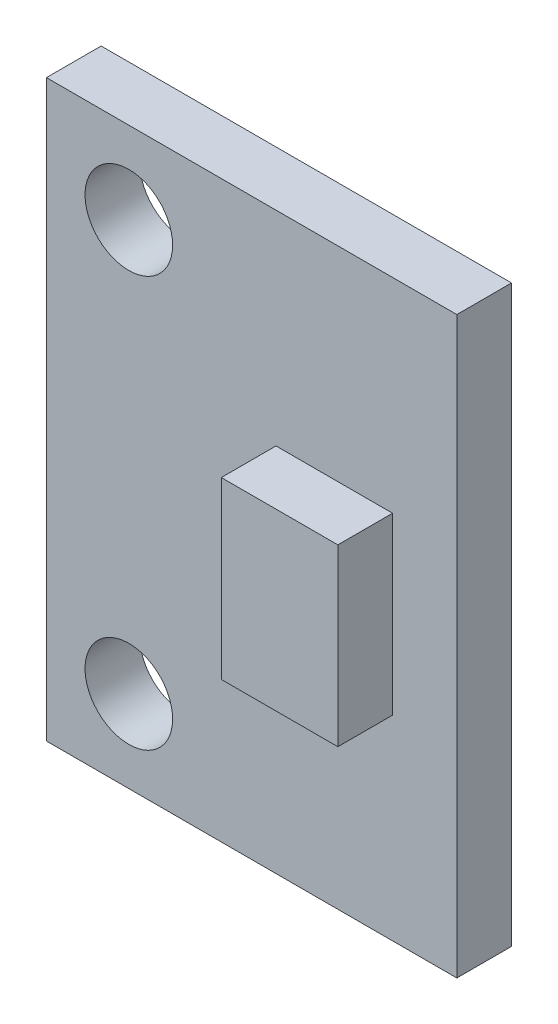
SolidWorks part; units mm, degrees
ref_plane "Front Plane" through (0, 0, 0) normal (0, 0, 1) x (1, 0, 0)
ref_plane "Top Plane" through (0, 0, 0) normal (0, 1, 0) x (1, 0, 0)
ref_plane "Right Plane" through (0, 0, 0) normal (1, 0, 0) x (0, 0, -1)
sketch "Sketch1" plane through (0, 0, 0) normal (0, 0, 1) x (1, 0, 0)
  line L0 (-81.4383, -168.3882) -> (-81.4383, -189.3882) construction
  line L1 (-84.4493, -168.3882) -> (-69.4493, -168.3882)
  line L2 (-84.4493, -168.3882) -> (-84.4493, -189.3882)
  line L3 (-84.4493, -189.3882) -> (-69.4493, -189.3882)
  line L4 (-69.4493, -168.3882) -> (-69.4493, -189.3882)
  line L5 (-84.4493, -178.8882) -> (-69.4493, -178.8882) construction
  circle A0 centre (-81.4383, -171.3882) radius 1.6
  circle A1 centre (-81.4383, -186.3882) radius 1.6
  dimension "D3" = 15
  dimension "D4" = 7.5
  dimension "D1" = 15
  dimension "D2" = 21
extrude "Boss-Extrude1" add sketch "Sketch1" along normal blind 2
sketch "Sketch2" plane through (0, 0, 2) normal (0, 0, 1) x (1, 0, 0)
  line L0 (-84.4493, -178.8882) -> (-69.4493, -178.8882) construction
  line L1 (-84.4493, -168.3882) -> (-84.4493, -189.3882) construction
  line L2 (-69.4493, -189.3882) -> (-69.4493, -168.3882) construction
  line L4 (-76.0588, -175.852) -> (-71.7986, -175.852)
  line L5 (-76.0588, -175.852) -> (-76.0588, -182.2423)
  line L6 (-76.0588, -182.2423) -> (-71.7986, -182.2423)
  line L7 (-71.7986, -175.852) -> (-71.7986, -182.2423)
extrude "Boss-Extrude2" add sketch "Sketch2" along normal blind 2
